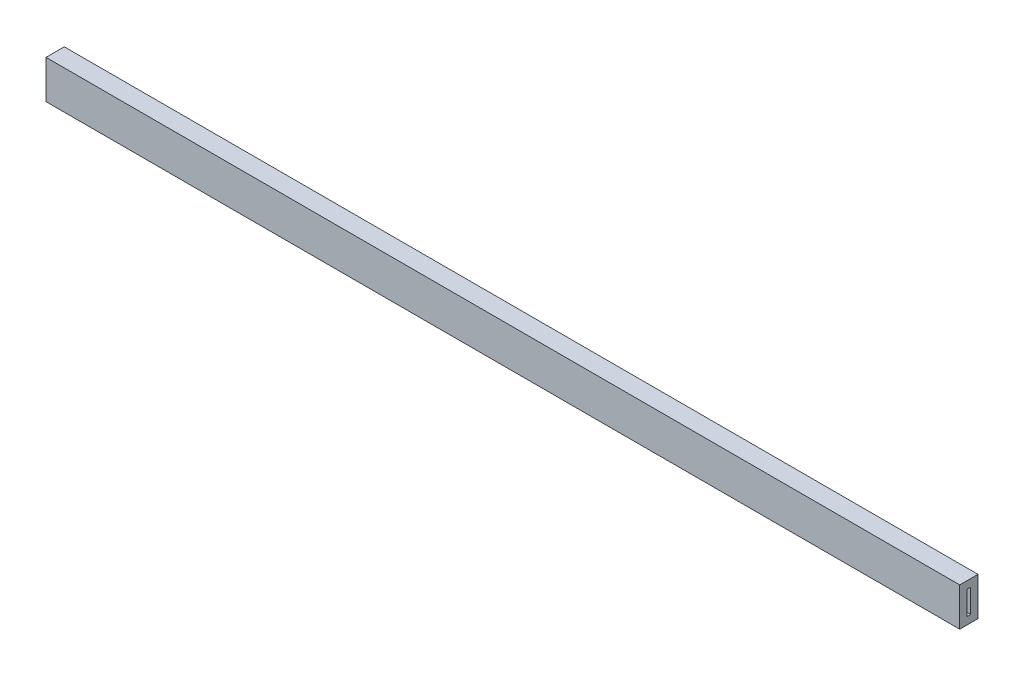
SolidWorks part; units mm, degrees
material "Thornel Mat VMA"
ref_plane "Front Plane" through (0, 0, 0) normal (0, 0, 1) x (1, 0, 0)
ref_plane "Top Plane" through (0, 0, 0) normal (0, 1, 0) x (1, 0, 0)
ref_plane "Right Plane" through (0, 0, 0) normal (1, 0, 0) x (0, 0, -1)
sketch "Sketch1" plane through (0, 0, 0) normal (1, 0, 0) x (0, 0, -1)
  line L1 (-1.5, -9.75) -> (1.5, -9.75)
  line L2 (-1.5, -9.75) -> (-1.5, 9.75)
  line L3 (-1.5, 9.75) -> (1.5, 9.75)
  line L4 (1.5, -9.75) -> (1.5, 9.75)
  line L5 (-1.5, -9.75) -> (1.5, 9.75) construction
  line L6 (-1.5, 9.75) -> (1.5, -9.75) construction
  line L7 (-7.5, -15.75) -> (7.5, -15.75)
  line L8 (-7.5, -15.75) -> (-7.5, 15.75)
  line L9 (-7.5, 15.75) -> (7.5, 15.75)
  line L10 (7.5, -15.75) -> (7.5, 15.75)
  line L11 (-7.5, -15.75) -> (7.5, 15.75) construction
  line L12 (-7.5, 15.75) -> (7.5, -15.75) construction
  point P0 (0, 0)
  point P6 (0, 0)
  dimension "D1" = 31.5
  dimension "D2" = 15
  dimension "D3" = 3
  dimension "D4" = 19.5
extrude "Boss-Extrude1" add sketch "Sketch1" along normal blind 750
equation "\"StrutHeight\" = 31.5"
equation "\"D1@Sketch1\"=\"StrutHeight\""
equation "\"StrutWidth\" = 15"
equation "\"D2@Sketch1\"=\"StrutWidth\""
equation "\"StrutWallThickness\"= 6"
equation "\"D3@Sketch1\"=\"StrutWidth\"-\"StrutWallThickness\"*2"
equation "\"D4@Sketch1\"=\"StrutHeight\"-\"StrutWallThickness\"*2"
equation "\"StrutLength\"=750"
equation "\"D1@Boss-Extrude1\"=\"StrutLength\""
